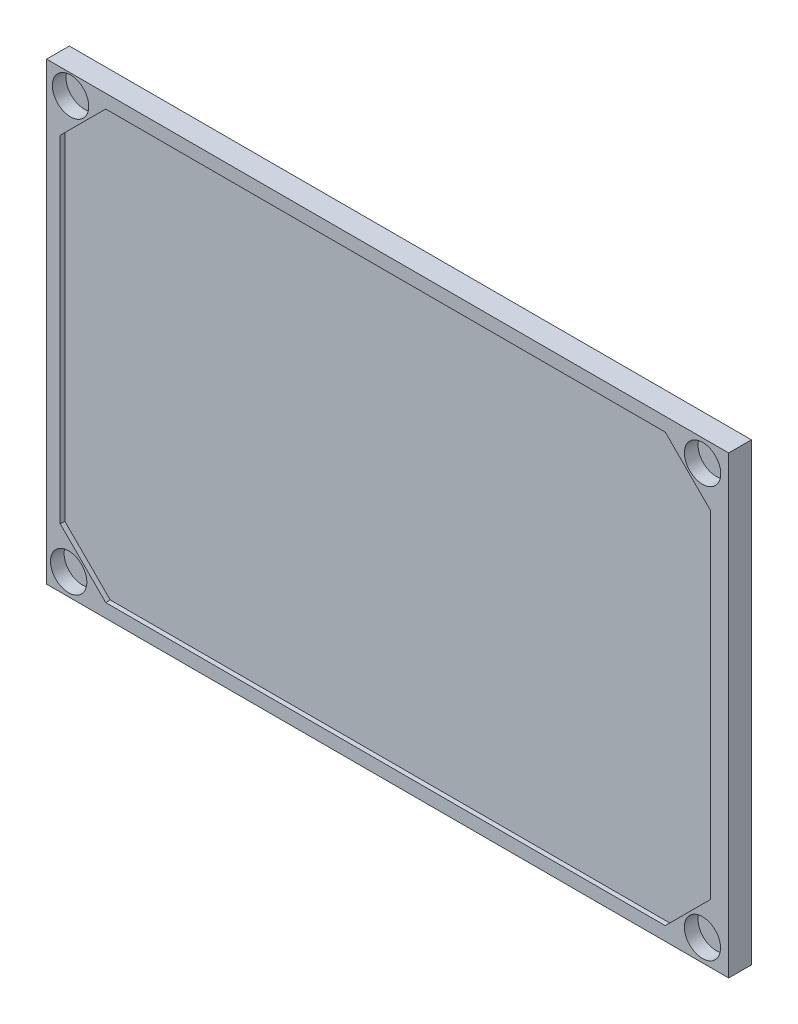
SolidWorks part; units mm, degrees
ref_plane "Plan de face" through (0, 0, 0) normal (0, 0, 1) x (1, 0, 0)
ref_plane "Plan de dessus" through (0, 0, 0) normal (0, 1, 0) x (1, 0, 0)
ref_plane "Plan de droite" through (0, 0, 0) normal (1, 0, 0) x (0, 0, -1)
sketch "Esquisse1" plane through (0, 0, 0) normal (0, 0, 1) x (1, 0, 0)
  line L1 (-96.1737, 39.2273) -> (53.8263, 39.2273)
  line L2 (-96.1737, 39.2273) -> (-96.1737, -60.7727)
  line L3 (-96.1737, -60.7727) -> (53.8263, -60.7727)
  line L4 (53.8263, 39.2273) -> (53.8263, -60.7727)
  dimension "D1" = 150
  dimension "D2" = 100
extrude "Boss.-Extru.1" add sketch "Esquisse1" along normal blind 5
sketch "Esquisse2" plane through (0, 0, 5) normal (0, 0, 1) x (1, 0, 0)
  line L0 (-96.1737, 39.2273) -> (-96.1737, -60.7727) construction
  line L1 (-83.1737, 36.2273) -> (39.8737, 36.2273)
  line L2 (-93.1737, 26.2273) -> (-93.1737, -47.7727)
  line L3 (-83.1737, -57.7727) -> (39.8737, -57.7727)
  line L4 (49.8737, 26.2273) -> (49.8737, -47.7727)
  line L5 (53.8263, 39.2273) -> (-96.1737, 39.2273) construction
  line L6 (53.8263, -60.7727) -> (53.8263, 39.2273) construction
  line L7 (-96.1737, -60.7727) -> (53.8263, -60.7727) construction
  line L8 (-83.1737, 36.2273) -> (-93.1737, 26.2273)
  line L9 (-93.1737, -47.7727) -> (-83.1737, -57.7727)
  line L10 (49.8737, -47.7727) -> (39.8737, -57.7727)
  line L11 (39.8737, 36.2273) -> (49.8737, 26.2273)
  point P0 (-93.1737, 36.2273)
  point P1 (49.8737, -57.7727)
  point P2 (-93.1737, -57.7727)
  point P3 (49.8737, 36.2273)
  dimension "D1" = 3
  dimension "D2" = 3
  dimension "D3" = 3.9526
  dimension "D4" = 3
extrude "Enlèv. mat.-Extru.1" cut sketch "Esquisse2" against normal blind 1
sketch "Esquisse3" plane through (0, 0, 5) normal (0, 0, 1) x (1, 0, 0)
  line L0 (-83.1737, 36.2273) -> (-93.1737, 26.2273) construction
  circle A0 centre (-90.9074, 34.8576) radius 4
  point P0 (-93.0653, 35.1934)
  point P1 (-87.729, 31.6721)
extrude "Enlèv. mat.-Extru.2" cut sketch "Esquisse3" against normal blind 3 contours A0
sketch "Esquisse6" plane through (0, 0, 5) normal (0, 0, 1) x (1, 0, 0)
  line L0 (49.8737, 26.2273) -> (39.8737, 36.2273) construction
  circle A0 centre (48.0833, 34.3814) radius 4
  point P0 (44.8737, 31.2273)
extrude "Enlèv. mat.-Extru.6" cut sketch "Esquisse6" against normal blind 3 contours A0
sketch "Esquisse7" plane through (0, 0, 5) normal (0, 0, 1) x (1, 0, 0)
  circle A0 centre (-91.323, -55.987) radius 4
extrude "Enlèv. mat.-Extru.8" cut sketch "Esquisse7" against normal blind 3 contours A0
sketch "Esquisse8" plane through (0, 0, 5) normal (0, 0, 1) x (1, 0, 0)
  line L0 (39.8737, -57.7727) -> (49.8737, -47.7727) construction
  circle A0 centre (48.0631, -55.9472) radius 3.9822
  point P0 (44.8744, -52.7719)
extrude "Enlèv. mat.-Extru.10" cut sketch "Esquisse8" against normal blind 3 contours A0
ref_plane "Plan8" [suppressed] through (-96.1737, 39.2273, 5) normal (0, 0, -1) x (-1, 0, 0)
sketch "Esquisse10" plane through (0, 0, 5) normal (0, 0, 1) x (1, 0, 0)
  line L0 (-93.1737, -47.7727) -> (-93.1737, -60.7727)
  line L1 (-96.1737, -60.7727) -> (53.8263, -60.7727) construction
  line L2 (-83.1737, -57.7727) -> (-96.1737, -57.7727)
  line L3 (-96.1737, 39.2273) -> (-96.1737, -60.7727) construction
